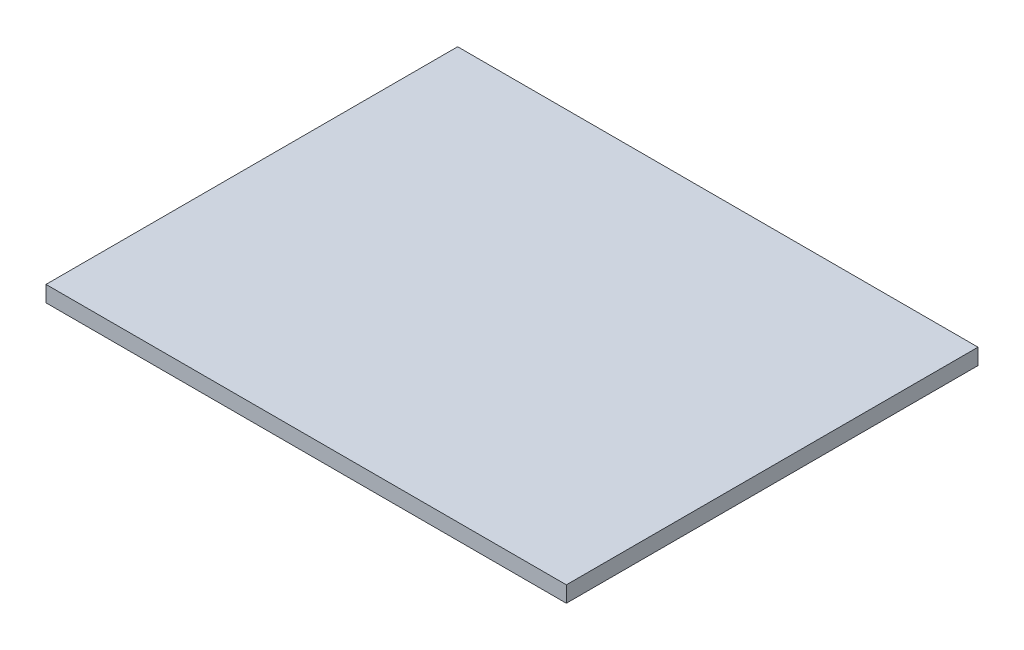
SolidWorks part; units mm, degrees
ref_plane "Front Plane" through (0, 0, 0) normal (0, 0, 1) x (1, 0, 0)
ref_plane "Top Plane" through (0, 0, 0) normal (0, 1, 0) x (1, 0, 0)
ref_plane "Right Plane" through (0, 0, 0) normal (1, 0, 0) x (0, 0, -1)
sketch "Sketch1" plane through (0, 0, 0) normal (0, 1, 0) x (1, 0, 0)
  line L1 (32.55, 25.75) -> (-32.55, 25.75)
  line L2 (32.55, 25.75) -> (32.55, -25.75)
  line L3 (32.55, -25.75) -> (-32.55, -25.75)
  line L4 (-32.55, 25.75) -> (-32.55, -25.75)
  line L5 (32.55, 25.75) -> (-32.55, -25.75) construction
  line L6 (32.55, -25.75) -> (-32.55, 25.75) construction
  point P0 (0, 0)
  dimension "D1" = 51.5
  dimension "D2" = 65.1
extrude "Boss-Extrude1" add sketch "Sketch1" along normal blind 2
